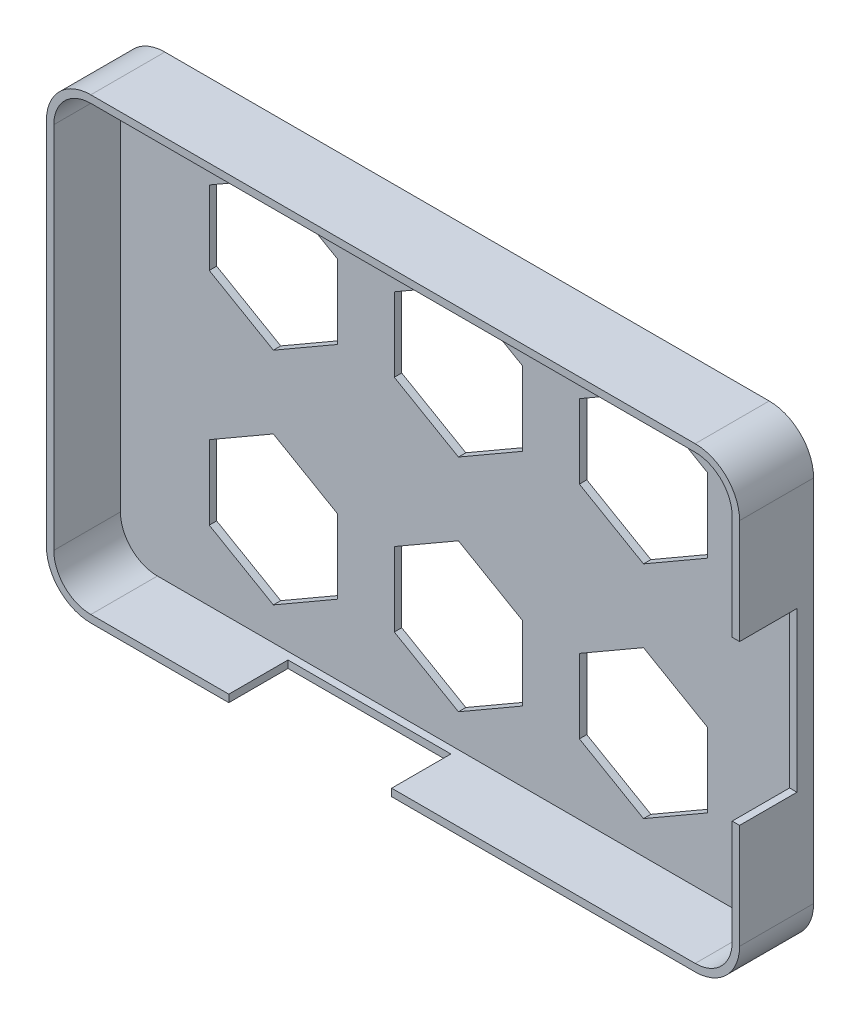
SolidWorks part; units mm, degrees
ref_plane "Ebene vorne" through (0, 0, 0) normal (1, 0, 0) x (0, 1, 0)
ref_plane "Ebene oben" through (0, 0, 0) normal (0, 0, 1) x (0, 1, 0)
ref_plane "Ebene rechts" through (0, 0, 0) normal (0, 1, 0) x (-1, 0, 0)
sketch "Skizze1" plane through (0, 0, 0) normal (0, 0, 1) x (0, 1, 0)
  line L0 (-30.9, -46.82) -> (30.9, -46.82)
  line L1 (-30.9, -46.82) -> (-30.9, 46.82)
  line L2 (-30.9, 46.82) -> (30.9, 46.82)
  line L3 (30.9, -46.82) -> (30.9, 46.82)
  line L4 (-30.9, -46.82) -> (30.9, 46.82) construction
  line L5 (-30.9, 46.82) -> (30.9, -46.82) construction
  point P0 (0, 0)
  dimension "D1" = 61.8
  dimension "D2" = 93.64
extrude "Aufsatz-Linear austragen1" add sketch "Skizze1" along normal blind 10
fillet "Verrundung1" radius 6 4 edges at (46.82, -30.9, 5) (-46.82, -30.9, 5) (-46.82, 30.9, 5) (46.82, 30.9, 5)
shell "Wandung1" thickness 1
sketch "Skizze2" plane through (46.82, 0, 0) normal (1, 0, 0) x (0, 1, 0)
  line L0 (-24.9, 10) -> (24.9, 10) construction
  line L1 (-10.75, 17.75) -> (10.75, 17.75)
  line L2 (-10.75, 17.75) -> (-10.75, 2.25)
  line L3 (-10.75, 2.25) -> (10.75, 2.25)
  line L4 (10.75, 17.75) -> (10.75, 2.25)
  line L5 (-10.75, 17.75) -> (10.75, 2.25) construction
  line L6 (-10.75, 2.25) -> (10.75, 17.75) construction
  point P0 (0, 10)
  dimension "D1" = 21.5
  dimension "D2" = 15.5
extrude "Schnitt-Linear austragen1" cut sketch "Skizze2" against normal blind 6
sketch "Skizze3" plane through (0, -30.9, 0) normal (0, -1, 0) x (1, 0, 0)
  line L0 (-40.82, 10) -> (40.82, 10) construction
  line L1 (-0.18, 10) -> (-22.18, 10)
  line L2 (-0.18, 10) -> (-0.18, 2)
  line L3 (-0.18, 2) -> (-22.18, 2)
  line L4 (-22.18, 10) -> (-22.18, 2)
  dimension "D1" = 22
  dimension "D2" = 8
  dimension "D3" = 41
extrude "Schnitt-Linear austragen2" cut sketch "Skizze3" against normal blind 6
sketch "Skizze4" plane through (0, 0, 0) normal (0, 0, -1) x (1, 0, 0)
  line L0 (-33.82, 30.9) -> (-33.82, -30.9) construction
  line L2 (-25.1597, 25.45) -> (-33.82, 20.45)
  line L3 (-33.82, 20.45) -> (-33.82, 10.45)
  line L4 (-33.82, 10.45) -> (-25.1597, 5.45)
  line L5 (-25.1597, 5.45) -> (-16.4995, 10.45)
  line L6 (-16.4995, 10.45) -> (-16.4995, 20.45)
  line L7 (-16.4995, 20.45) -> (-25.1597, 25.45)
  line L8 (-25.1597, -4.35) -> (-33.82, -9.35)
  line L9 (-33.82, -9.35) -> (-33.82, -19.35)
  line L10 (-33.82, -19.35) -> (-25.1597, -24.35)
  line L11 (-25.1597, -24.35) -> (-16.4995, -19.35)
  line L12 (-16.4995, -19.35) -> (-16.4995, -9.35)
  line L13 (-16.4995, -9.35) -> (-25.1597, -4.35)
  line L14 (-46.82, -24.9) -> (-46.82, 24.9) construction
  circle A8 centre (-25.1597, 15.45) radius 8.6603 construction
  dimension "D3" = 10.45
  dimension "D4" = 2
  dimension "D5" = 13
  dimension "D1" = 10
  dimension "D2" = 61.8
extrude "Schnitt-Linear austragen4" cut sketch "Skizze4" against normal blind 6
pattern_linear "Lineares Muster1" count 3 spacing 25 along (1, 0, 0) of "Schnitt-Linear austragen4"
